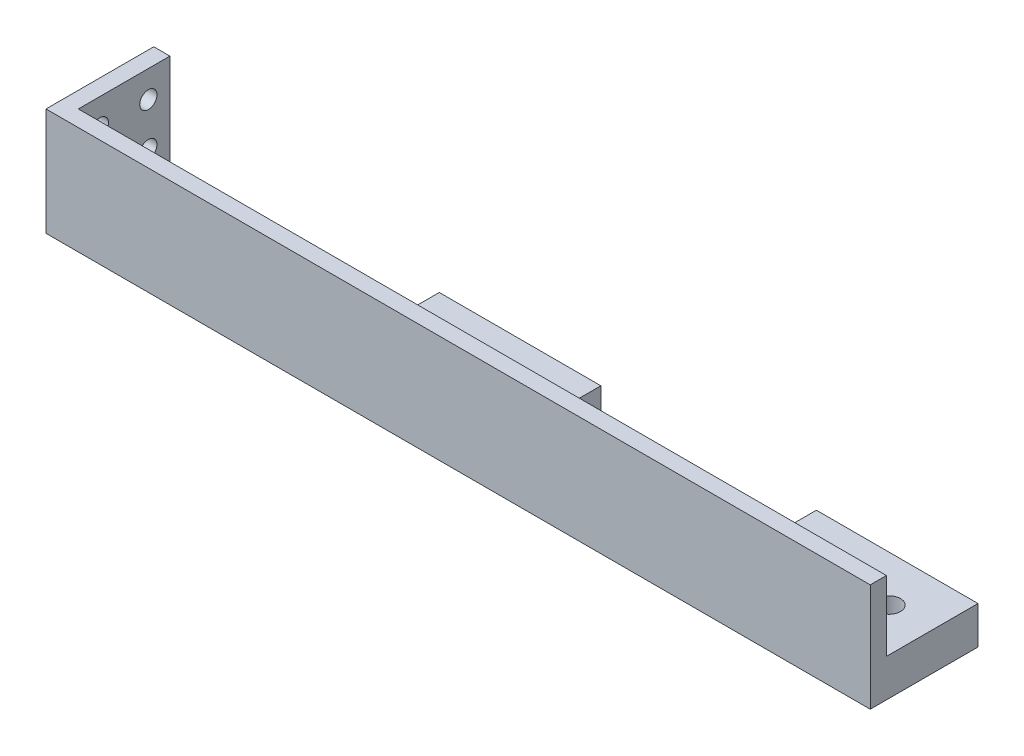
SolidWorks part; units mm, degrees
ref_plane "Front Plane" through (0, 0, 0) normal (0, 0, 1) x (1, 0, 0)
ref_plane "Top Plane" through (0, 0, 0) normal (0, 1, 0) x (1, 0, 0)
ref_plane "Right Plane" through (0, 0, 0) normal (1, 0, 0) x (0, 0, -1)
sketch "Sketch1" plane through (0, 0, 0) normal (0, 0, 1) x (1, 0, 0)
  line L1 (88.4016, -22.1754) -> (241.4016, -22.1754)
  line L2 (88.4016, -22.1754) -> (88.4016, -42.1754)
  line L3 (88.4016, -42.1754) -> (241.4016, -42.1754)
  line L4 (241.4016, -22.1754) -> (241.4016, -42.1754)
  dimension "D1" = 20
  dimension "D2" = 153
extrude "Boss-Extrude1" add sketch "Sketch1" along normal blind 3
sketch "Sketch2" plane through (0, 0, 0) normal (0, 0, -1) x (-1, 0, 0)
  line L0 (-88.4016, -42.1754) -> (-241.4016, -42.1754) construction
  line L1 (-88.4016, -22.1754) -> (-91.4016, -22.1754)
  line L2 (-88.4016, -22.1754) -> (-88.4016, -42.1754)
  line L3 (-88.4016, -42.1754) -> (-91.4016, -42.1754)
  line L4 (-91.4016, -22.1754) -> (-91.4016, -42.1754)
  dimension "D1" = 3
extrude "Boss-Extrude2" add sketch "Sketch2" along normal blind 17
sketch "Sketch3" plane through (0, 0, 0) normal (0, 0, -1) x (-1, 0, 0)
  line L0 (-241.4016, -42.1754) -> (-241.4016, -22.1754) construction
  line L1 (-91.4016, -42.1754) -> (-241.4016, -42.1754)
  line L2 (-91.4016, -42.1754) -> (-91.4016, -39.1754)
  line L3 (-91.4016, -39.1754) -> (-241.4016, -39.1754)
  line L4 (-241.4016, -42.1754) -> (-241.4016, -39.1754)
  dimension "D1" = 3
extrude "Boss-Extrude3" add sketch "Sketch3" along normal blind 17
sketch "Sketch4" plane through (88.4016, 0, 0) normal (-1, 0, 0) x (0, 0, 1)
  circle A0 centre (-13, -27.1754) radius 1.6
  circle A1 centre (-4, -27.1754) radius 1.6
  circle A2 centre (-4, -35.1754) radius 1.6
  circle A3 centre (-13, -35.1754) radius 1.5984
extrude "Cut-Extrude1" cut sketch "Sketch4" against normal blind 10
sketch "Sketch6" plane through (0, -39.1754, 0) normal (0, 1, 0) x (1, 0, 0)
  line L0 (241.4016, 0) -> (91.4016, 0) construction
  line L1 (241.4016, 17) -> (211.4016, 17)
  line L2 (241.4016, 17) -> (241.4016, 0)
  line L3 (241.4016, 0) -> (211.4016, 0)
  line L4 (211.4016, 17) -> (211.4016, 0)
  dimension "D1" = 30
extrude "Boss-Extrude4" add sketch "Sketch6" along normal blind 4
sketch "Sketch7" plane through (0, -35.1754, 0) normal (0, 1, 0) x (1, 0, 0)
  line L0 (241.4016, 17) -> (211.4016, 17) construction
  line L1 (241.4016, 0) -> (241.4016, 17) construction
  circle A0 centre (219.4016, 8.5) radius 2.1
  circle A1 centre (233.4016, 8.5) radius 2.1
  dimension "D1" = 4.2
  dimension "D2" = 4.2
  dimension "D3" = 8.5
  dimension "D4" = 8.5
  dimension "D5" = 8
  dimension "D6" = 22
extrude "Cut-Extrude3" cut sketch "Sketch7" against normal through all
sketch "Sketch8" plane through (0, -42.1754, 0) normal (0, -1, 0) x (1, 0, 0)
  circle A0 centre (219.4016, -8.5) radius 4
  circle A1 centre (233.4016, -8.5) radius 4
  dimension "D1" = 8
  dimension "D2" = 8
extrude "Cut-Extrude4" cut sketch "Sketch8" against normal blind 2.5
sketch "Sketch9" plane through (0, -39.1754, 0) normal (0, 1, 0) x (1, 0, 0)
  line L0 (91.4016, 17) -> (211.4016, 17) construction
  line L1 (141.4016, 17) -> (171.4016, 17)
  line L2 (141.4016, 17) -> (141.4016, 0)
  line L3 (141.4016, 0) -> (171.4016, 0)
  line L4 (171.4016, 17) -> (171.4016, 0)
  line L5 (241.4016, 0) -> (91.4016, 0) construction
  line L6 (241.4016, 0) -> (241.4016, 17) construction
  dimension "D1" = 70
  dimension "D2" = 30
extrude "Boss-Extrude5" add sketch "Sketch9" along normal up to surface (4 mm away) up to face at (219.4016, -35.1754, -6.4)
sketch "Sketch12" plane through (0, -35.1754, 0) normal (0, 1, 0) x (1, 0, 0)
  line L0 (171.4016, 17) -> (171.4016, 0) construction
  line L1 (141.4016, 0) -> (141.4016, 17) construction
  line L2 (241.4016, 0) -> (91.4016, 0) construction
  circle A0 centre (163.4016, 8.5) radius 2.1
  circle A1 centre (149.4016, 8.5) radius 2.1
  dimension "D1" = 4.2
  dimension "D2" = 4.2
  dimension "D3" = 8
  dimension "D4" = 8
  dimension "D5" = 8.5
  dimension "D6" = 8.5
extrude "Cut-Extrude7" cut sketch "Sketch12" against normal through all
sketch "Sketch13" plane through (0, -42.1754, 0) normal (0, -1, 0) x (1, 0, 0)
  circle A0 centre (163.4016, -8.5) radius 4
  circle A1 centre (149.4016, -8.5) radius 4
  dimension "D1" = 8
  dimension "D2" = 8
extrude "Cut-Extrude8" cut sketch "Sketch13" against normal blind 2.5
chamfer "Chamfer9" distance 3 angle 45 2 edges at (116.4016, -39.1754, 0) (191.4016, -39.1754, 0)
sketch "Sketch15" plane through (0, -39.1754, 0) normal (0, 1, 0) x (1, 0, 0)
  line L0 (171.4016, 17) -> (211.4016, 17) construction
  line L1 (211.4016, 0) -> (208.3016, 0)
  line L2 (211.4016, 0) -> (211.4016, 17)
  line L3 (211.4016, 17) -> (208.3016, 17)
  line L4 (208.3016, 0) -> (208.3016, 17)
  line L5 (91.4016, 17) -> (141.4016, 17) construction
  line L6 (174.5016, 17) -> (171.4016, 17)
  line L7 (174.5016, 17) -> (174.5016, 0)
  line L8 (174.5016, 0) -> (171.4016, 0)
  line L9 (171.4016, 17) -> (171.4016, 0)
  line L10 (138.3016, 17) -> (141.4016, 17)
  line L11 (138.3016, 17) -> (138.3016, 0)
  line L12 (138.3016, 0) -> (141.4016, 0)
  line L13 (141.4016, 17) -> (141.4016, 0)
  dimension "D1" = 3.1
  dimension "D2" = 3.1
  dimension "D3" = 3.1
extrude "Cut-Extrude10" cut sketch "Sketch15" along normal blind 3
